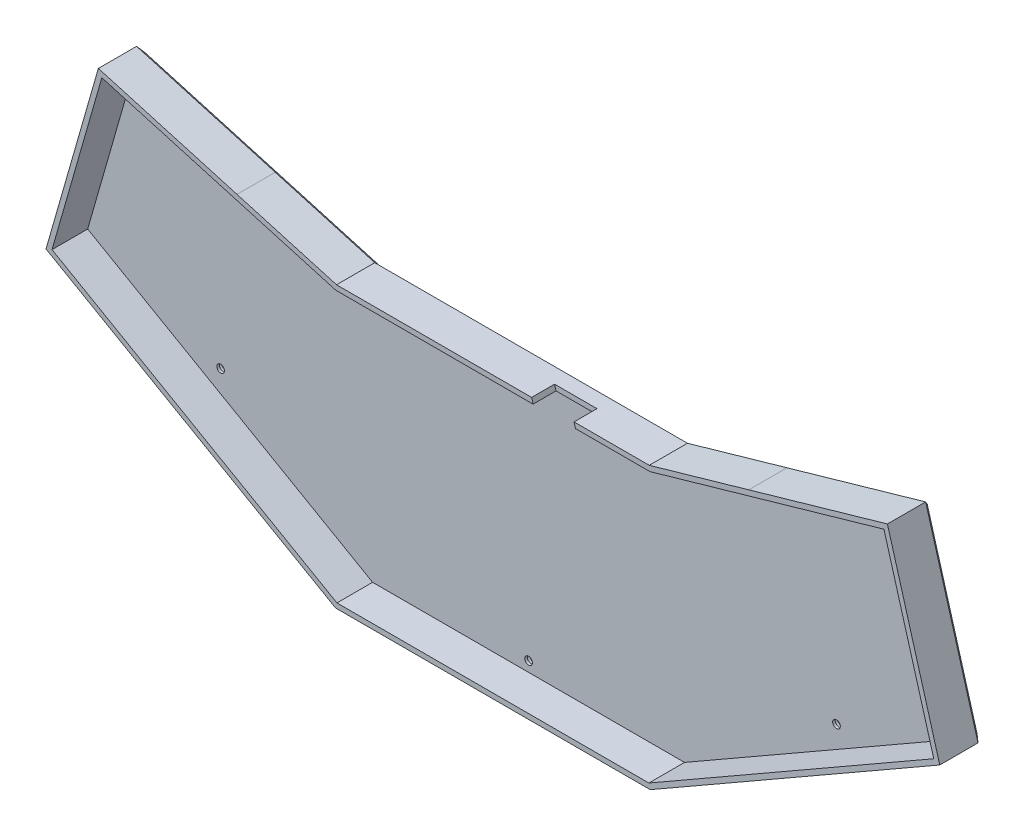
SolidWorks part; units mm, degrees
ref_plane "Plan de face" through (0, 0, 0) normal (0, 0, 1) x (1, 0, 0)
ref_plane "Plan de dessus" through (0, 0, 0) normal (0, 1, 0) x (1, 0, 0)
ref_plane "Plan de droite" through (0, 0, 0) normal (1, 0, 0) x (0, 0, -1)
sketch "Esquisse1" plane through (0, 0, 0) normal (0, 0, 1) x (1, 0, 0)
  line L0 (229.1572, -14.8472) -> (106.4333, -14.8472)
  line L1 (106.4333, -14.8472) -> (67.3725, -3.6491)
  line L2 (67.3725, -3.6491) -> (12.9612, 11.9531)
  line L3 (12.9612, 11.9531) -> (-7.5845, -59.6983)
  line L4 (-7.5845, -59.6983) -> (106.0528, -124.8987)
  line L5 (106.0528, -124.8987) -> (229.5377, -124.8987)
  line L6 (229.5377, -124.8987) -> (343.175, -59.6983)
  line L7 (343.175, -59.6983) -> (322.6293, 11.9531)
  line L8 (322.6293, 11.9531) -> (268.218, -3.6491)
  line L9 (268.218, -3.6491) -> (229.1572, -14.8472)
  line L10 (229.4382, -16.8472) -> (106.1523, -16.8472)
  line L11 (106.1523, -16.8472) -> (66.8213, -5.5716)
  line L12 (66.8213, -5.5716) -> (14.3325, 9.4793)
  line L13 (14.3325, 9.4793) -> (-5.2301, -58.7434)
  line L14 (-5.2301, -58.7434) -> (106.5858, -122.8987)
  line L15 (106.5858, -122.8987) -> (229.0047, -122.8987)
  line L16 (229.0047, -122.8987) -> (340.8206, -58.7434)
  line L17 (340.8206, -58.7434) -> (321.2581, 9.4793)
  line L18 (321.2581, 9.4793) -> (268.7692, -5.5716)
  line L19 (268.7692, -5.5716) -> (229.4382, -16.8472)
  line L20 (322.9036, 12.4479) -> (268.1078, -3.2646) construction
  line L21 (268.1078, -3.2646) -> (229.101, -14.4472) construction
  line L22 (229.101, -14.4472) -> (106.4895, -14.4472) construction
  line L23 (106.4895, -14.4472) -> (67.4828, -3.2646) construction
  line L24 (67.4828, -3.2646) -> (12.687, 12.4479) construction
  line L25 (12.687, 12.4479) -> (-8.0554, -59.8893) construction
  line L26 (-8.0554, -59.8893) -> (105.9462, -125.2987) construction
  line L27 (105.9462, -125.2987) -> (229.6443, -125.2987) construction
  line L28 (229.6443, -125.2987) -> (343.6459, -59.8893) construction
  line L29 (343.6459, -59.8893) -> (322.9036, 12.4479) construction
  line L56 (242.979, -13.5895) -> (243.599, -15.7518) construction
  line L57 (243.599, -15.7518) -> (225.3337, -20.9893) construction
  line L58 (225.3337, -20.9893) -> (226.0229, -23.3926) construction
  line L59 (226.0229, -23.3926) -> (207.7584, -28.6299) construction
  line L60 (207.7584, -28.6299) -> (222.15, -78.8204) construction
  line L61 (222.15, -78.8204) -> (204.6471, -96.9784) construction
  line L62 (204.6471, -96.9784) -> (206.8614, -99.0254) construction
  line L63 (206.8614, -99.0254) -> (229.5776, -121.055) construction
  line L64 (229.5776, -121.055) -> (243.8282, -106.3374) construction
  line L65 (243.8282, -106.3374) -> (278.7547, -90.4535) construction
  line L66 (278.7547, -90.4535) -> (284.9301, -73.6049) construction
  line L67 (284.9301, -73.6049) -> (339.9352, -57.8324) construction
  line L68 (339.9352, -57.8324) -> (322.7757, 2.0099) construction
  line L69 (322.7757, 2.0099) -> (286.2451, -8.465) construction
  line L70 (286.2451, -8.465) -> (284.9358, -3.8987) construction
  line L71 (284.9358, -3.8987) -> (266.6705, -9.1362) construction
  line L72 (266.6705, -9.1362) -> (266.0508, -6.9751) construction
  line L73 (266.0508, -6.9751) -> (242.979, -13.5895) construction
  line L92 (91.9915, -15.7518) -> (92.6116, -13.5895) construction
  line L93 (92.6116, -13.5895) -> (69.5397, -6.9751) construction
  line L94 (69.5397, -6.9751) -> (68.92, -9.1362) construction
  line L95 (68.92, -9.1362) -> (50.6547, -3.8987) construction
  line L96 (50.6547, -3.8987) -> (49.3454, -8.465) construction
  line L97 (49.3454, -8.465) -> (12.8148, 2.0099) construction
  line L98 (12.8148, 2.0099) -> (-4.3447, -57.8324) construction
  line L99 (-4.3447, -57.8324) -> (50.6605, -73.6049) construction
  line L100 (50.6605, -73.6049) -> (56.8358, -90.4535) construction
  line L101 (56.8358, -90.4535) -> (91.7623, -106.3374) construction
  line L102 (91.7623, -106.3374) -> (106.0129, -121.055) construction
  line L103 (106.0129, -121.055) -> (128.7291, -99.0254) construction
  line L104 (128.7291, -99.0254) -> (130.9434, -96.9784) construction
  line L105 (130.9434, -96.9784) -> (113.4405, -78.8204) construction
  line L106 (113.4405, -78.8204) -> (127.8321, -28.6299) construction
  line L107 (127.8321, -28.6299) -> (109.5676, -23.3926) construction
  line L108 (109.5676, -23.3926) -> (110.2568, -20.9893) construction
  line L109 (110.2568, -20.9893) -> (91.9915, -15.7518) construction
  dimension "D1" = 0.4
  dimension "D2" = 2
extrude "Boss.-Extru.1" add sketch "Esquisse1" along normal blind 14
sketch "Esquisse2" plane through (0, 0, 0) normal (0, 0, -1) x (-1, 0, 0)
  line L10 (-229.1572, -14.8472) -> (-268.218, -3.6491)
  line L11 (-268.218, -3.6491) -> (-322.6293, 11.9531)
  line L12 (-322.6293, 11.9531) -> (-343.175, -59.6983)
  line L13 (-343.175, -59.6983) -> (-229.5377, -124.8987)
  line L14 (-229.5377, -124.8987) -> (-106.0528, -124.8987)
  line L15 (-106.0528, -124.8987) -> (7.5845, -59.6983)
  line L16 (7.5845, -59.6983) -> (-12.9612, 11.9531)
  line L17 (-12.9612, 11.9531) -> (-67.3725, -3.6491)
  line L18 (-67.3725, -3.6491) -> (-106.4333, -14.8472)
  line L19 (-106.4333, -14.8472) -> (-229.1572, -14.8472)
  line L20 (-229.1572, -14.8472) -> (-268.218, -3.6491)
  line L21 (-268.218, -3.6491) -> (-322.6293, 11.9531)
  line L22 (-322.6293, 11.9531) -> (-343.175, -59.6983)
  line L23 (-343.175, -59.6983) -> (-229.5377, -124.8987)
  line L24 (-229.5377, -124.8987) -> (-106.0528, -124.8987)
  line L25 (-106.0528, -124.8987) -> (7.5845, -59.6983)
  line L26 (7.5845, -59.6983) -> (-12.9612, 11.9531)
  line L27 (-12.9612, 11.9531) -> (-67.3725, -3.6491)
  line L28 (-67.3725, -3.6491) -> (-106.4333, -14.8472)
  line L29 (-106.4333, -14.8472) -> (-229.1572, -14.8472)
  dimension "D1" = 0
extrude "Boss.-Extru.2" add sketch "Esquisse2" along normal blind 3
sketch "Esquisse3" plane through (0, 0, 0) normal (0, 0, 1) x (1, 0, 0)
  line L30 (193.384, 6.9885) -> (218.3049, -79.923)
  line L31 (164.5068, 7.668) -> (229.6158, 6.136) construction
  line L32 (203.9133, -29.7324) -> (218.3049, -79.923) construction
  line L33 (178.0038, 2.5784) -> (202.9247, -84.3331)
  line L34 (202.9247, -84.3331) -> (218.3049, -79.923)
  line L35 (193.384, 6.9885) -> (178.0038, 2.5784)
  line L60 (207.7584, -28.6299) -> (222.15, -78.8204) construction
  dimension "D1" = 4
  dimension "D2" = 16
extrude "Enlèv. mat.-Extru.1" cut sketch "Esquisse3" along normal blind 10 from offset 5
sketch "Esquisse7" plane through (0, 0, 0) normal (0, 0, 1) x (1, 0, 0)
  line L0 (321.2581, 9.4793) -> (311.6454, 6.7229) construction
  line L1 (321.2581, 9.4793) -> (268.7692, -5.5716) construction
  line L2 (311.6454, 6.7229) -> (312.748, 2.8779) construction
  line L3 (106.1523, -16.8472) -> (229.4382, -16.8472) construction
  line L4 (167.7953, -16.8472) -> (167.7953, -20.8472) construction
  line L5 (167.7953, -16.8472) -> (167.7953, -122.8987) construction
  line L6 (106.5858, -122.8987) -> (229.0047, -122.8987) construction
  line L7 (167.7953, -69.873) -> (175.0532, -69.873) construction
  line L8 (50.6605, -73.6049) -> (43.2333, -86.5497) construction
  line L10 (50.6605, -73.6049) -> (46.9469, -80.0773) construction
  line L11 (-5.2301, -58.7434) -> (106.5858, -122.8987) construction
  circle A0 centre (312.748, 2.8779) radius 1.5
  circle A1 centre (167.7953, -20.8472) radius 1.5
  circle A2 centre (22.8425, 2.8779) radius 1.5
  circle A3 centre (167.7953, -118.8987) radius 1.5
  circle A4 centre (46.9469, -80.0773) radius 1.5
  circle A5 centre (288.6436, -80.0773) radius 1.5
extrude "Enlèv. mat.-Extru.2" cut sketch "Esquisse7" against normal blind 10
sketch "Esquisse8" plane through (0, 0, -3) normal (0, 0, -1) x (-1, 0, 0)
  circle A5 centre (-288.6436, -80.0773) radius 1.5 construction
  circle A6 centre (-22.8425, 2.8779) radius 3
  circle A7 centre (-46.9469, -80.0773) radius 3
  circle A8 centre (-167.7953, -118.8987) radius 3
  circle A9 centre (-167.7953, -20.8472) radius 3
  circle A10 centre (-288.6436, -80.0773) radius 3
  circle A11 centre (-312.748, 2.8779) radius 3
  circle A12 centre (-46.9469, -80.0773) radius 1.5 construction
extrude "Enlèv. mat.-Extru.3" cut sketch "Esquisse8" against normal blind 2
chamfer "Chanfrein1" distance 2 angle 45 10 edges at (86.9029, -9.2482, -3) (40.1669, 4.152, -3) (2.6884, -23.8726, -3) (49.2341, -92.2985, -3) (167.7953, -124.8987, -3) (286.3564, -92.2985, -3) (332.9022, -23.8726, -3) (295.4237, 4.152, -3) (248.6876, -9.2482, -3) (167.7953, -14.8472, -3)
